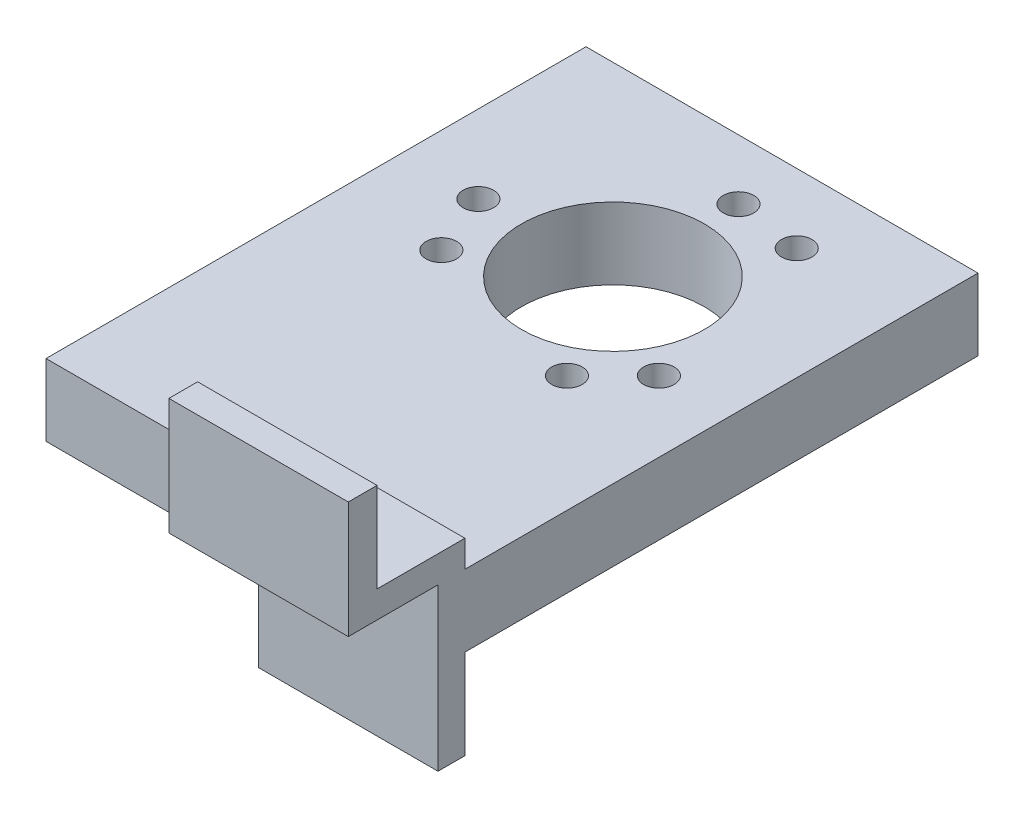
SolidWorks part; units mm, degrees
ref_plane "Front Plane" through (0, 0, 0) normal (0, 0, 1) x (1, 0, 0)
ref_plane "Top Plane" through (0, 0, 0) normal (0, 1, 0) x (1, 0, 0)
ref_plane "Right Plane" through (0, 0, 0) normal (1, 0, 0) x (0, 0, -1)
sketch "Sketch1" plane through (0, 0, 0) normal (0, 1, 0) x (1, 0, 0)
  line L0 (0, 0) -> (0, 39.5)
  line L1 (20, 0) -> (0, 0)
  line L2 (-23.7, 0) -> (0, 0)
  line L3 (0, 39.5) -> (0, 53.5)
  line L4 (0, 39.5) -> (-12.1244, 32.5)
  line L5 (0, 39.5) -> (12.1244, 32.5)
  line L6 (0, 39.5) -> (7.5, 52.4904)
  line L7 (0, 39.5) -> (-15, 39.5)
  line L8 (0, 39.5) -> (7, 27.3756)
  line L9 (15, 39.5) -> (20, 39.5)
  line L10 (20, 39.5) -> (20, 0)
  line L11 (0, 55.2) -> (0, 60.2)
  line L12 (20, 39.5) -> (20, 60.2)
  line L13 (20, 60.2) -> (0, 60.2)
  line L14 (-23.7, 0) -> (-23.7, 60.2)
  line L15 (-23.7, 60.2) -> (0, 60.2)
  circle A0 centre (0, 39.5) radius 10.2
  circle A1 centre (0, 39.5) radius 14
  circle A2 centre (0, 39.5) radius 15
  circle A3 centre (0, 53.5) radius 1.7
  circle A4 centre (7.5, 52.4904) radius 1.7
  circle A5 centre (12.1244, 32.5) radius 1.7
  circle A6 centre (7, 27.3756) radius 1.7
  circle A7 centre (-15, 39.5) radius 1.7
  circle A8 centre (-12.1244, 32.5) radius 1.7
extrude "Boss-Extrude2" add sketch "Sketch1" along normal blind 8 contours A4 A2 A3 A1 | A7 A1 A3 A2 | A8 A1 A7 A2 | A5 A2 A4 A1 | A8 A2 L0 A1 | A6 A1 L0 A2 | A6 A2 A5 A1 | A8 L4 A0 L7 A7 A1 | A7 L7 A0 L3 A3 A1 | A4 A1 A3 L3 A0 L6 | A5 A1 A4 L6 A0 L5 | A6 A1 A5 L5 A0 L8 | A6 L8 A0 L0 A1 | A8 A1 L0 A0 L4 | A8 A2 A7 A3 L11 L15 L14 L2 L0 | A4 A2 L9 L12 L13 L11 A3 | A6 A2 L0 L1 L10 L9 A5
sketch "Sketch7" plane through (0, 0, 0) normal (0, -1, 0) x (1, 0, 0)
  line L1 (20, 0) -> (0, 0)
  line L2 (20, 0) -> (20, -3)
  line L3 (20, -3) -> (0, -3)
  line L4 (0, 0) -> (0, -3)
extrude "Boss-Extrude7" add sketch "Sketch7" along normal blind 10
sketch "Sketch8" plane through (0, 8, 0) normal (0, 1, 0) x (1, 0, 0)
  line L1 (20, 0) -> (0, 0)
  line L2 (20, 0) -> (20, 3)
  line L3 (20, 3) -> (0, 3)
  line L4 (0, 0) -> (0, 3)
extrude "Boss-Extrude8" add sketch "Sketch8" along normal blind 3
sketch "Sketch9" plane through (0, 0, 0) normal (0, 0, 1) x (1, 0, 0)
  line L1 (0, 11) -> (20, 11)
  line L2 (0, 11) -> (0, 8)
  line L3 (0, 8) -> (20, 8)
  line L4 (20, 11) -> (20, 8)
extrude "Boss-Extrude9" add sketch "Sketch9" along normal blind 10
sketch "Sketch10" plane through (0, 11, 0) normal (0, 1, 0) x (1, 0, 0)
  line L0 (20, -10) -> (20, 3) construction
  line L1 (0, -10) -> (20, -10)
  line L2 (0, -10) -> (0, -6.7968)
  line L3 (0, -6.7968) -> (20, -6.7968)
  line L4 (20, -10) -> (20, -6.7968)
extrude "Boss-Extrude10" add sketch "Sketch10" along normal blind 10
